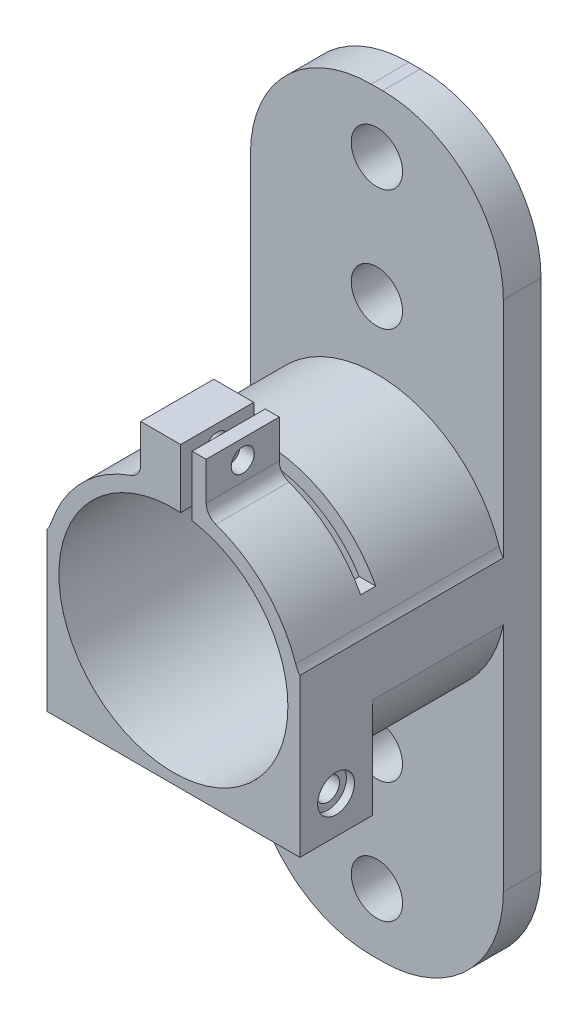
SolidWorks part; units mm, degrees
ref_plane "Front Plane" through (0, 0, 0) normal (0, 0, 1) x (1, 0, 0)
ref_plane "Top Plane" through (0, 0, 0) normal (0, 1, 0) x (1, 0, 0)
ref_plane "Right Plane" through (0, 0, 0) normal (1, 0, 0) x (0, 0, -1)
sketch "Sketch1" plane through (0, 0, 0) normal (0, 0, 1) x (1, 0, 0)
  line L0 (-13.97, 0) -> (13.97, 0)
  line L1 (13.97, 0) -> (13.97, 17.4151)
  line L2 (13.97, 28.0162) -> (-13.97, 28.0162) construction
  line L3 (-13.97, 17.4151) -> (-13.97, 0)
  line L4 (0, 0) -> (0, 32.6948) construction
  arc A0 (13.5022, 18.2934) -> (-13.5022, 18.2934) centre (0, 13.7795) ccw
  arc A1 (-13.97, 17.4151) -> (-13.5022, 18.2934) centre (-16.3447, 19.2437) ccw
  arc A2 (13.97, 17.4151) -> (13.5022, 18.2934) centre (16.3447, 19.2437) cw
  dimension "D4" = 28.4734
  dimension "D6" = 5.9944
  dimension "D1" = 27.94
  dimension "D2" = 13.97
  dimension "D3" = 28.0162
  dimension "D5" = 13.7795
extrude "Boss-Extrude1" add sketch "Sketch1" against normal blind 55.499
sketch "Sketch2" plane through (0, 0, 0) normal (0, 0, 1) x (1, 0, 0)
  circle A0 centre (0, 13.7795) radius 12.6492
  dimension "D1" = 25.2984
extrude "Cut-Extrude1" cut sketch "Sketch2" against normal blind 21.082
sketch "Sketch3" plane through (0, 0, -55.499) normal (0, 0, -1) x (-1, 0, 0)
  line L0 (-13.97, 0) -> (-13.97, 17.4151) construction
  line L1 (13.97, 0) -> (-13.97, 0) construction
  line L2 (13.97, 17.4151) -> (13.97, 0) construction
  line L3 (-13.97, 0) -> (-13.97, 11.0367)
  line L4 (13.97, 0) -> (3.579, 0)
  line L5 (13.97, 11.0367) -> (13.97, 0)
  line L6 (-3.579, 0) -> (-13.97, 0)
  arc A0 (-13.97, 11.0367) -> (-3.579, 0) centre (0, 13.7795) ccw
  arc A1 (3.579, 0) -> (13.97, 11.0367) centre (0, 13.7795) ccw
extrude "Cut-Extrude2" cut sketch "Sketch3" against normal blind 47.498
sketch "Sketch4" plane through (0, 0, 0) normal (0, 1, 0) x (1, 0, 0)
  line L0 (0, 60.4988) -> (0, 6.2072) construction
  line L1 (-10.033, 46.5201) -> (-10.033, 26.4795)
  line L2 (10.033, 46.5201) -> (10.033, 26.4795)
  line L3 (-6.0325, 50.5206) -> (6.0325, 50.5206)
  line L4 (6.0325, 22.479) -> (-6.0325, 22.479)
  line L5 (-10.033, 60.4988) -> (-10.033, 6.2072) construction
  line L6 (10.033, 60.4988) -> (10.033, 6.2072) construction
  line L7 (13.5022, 55.499) -> (-13.5022, 55.499) construction
  line L8 (-13.5022, 0) -> (13.5022, 0) construction
  arc A0 (-10.033, 46.5201) -> (-6.0325, 50.5206) centre (-6.0325, 46.5201) cw
  arc A1 (6.0325, 50.5206) -> (10.033, 46.5201) centre (6.0325, 46.5201) cw
  arc A2 (10.033, 26.4795) -> (6.0325, 22.479) centre (6.0325, 26.4795) cw
  arc A3 (-6.0325, 22.479) -> (-10.033, 26.4795) centre (-6.0325, 26.4795) cw
  dimension "D5" = 4.0005
  dimension "D3" = 4.9784
  dimension "D4" = 22.479
  dimension "D1" = 10.033
  dimension "D2" = 10.033
extrude "Cut-Extrude3" cut sketch "Sketch4" along normal through all
sketch "Sketch5" plane through (13.97, 0, 0) normal (1, 0, 0) x (0, 0, -1)
  line L0 (22.479, 26.6749) -> (22.479, 0.8841) construction
  line L1 (22.479, 30.5529) -> (22.479, 23.1262)
  line L2 (26.479, 19.1262) -> (58.3801, 19.1262)
  line L3 (22.479, 28.0162) -> (0, 28.0162) construction
  line L4 (22.479, 30.5529) -> (58.3801, 30.5529)
  line L5 (58.3801, 30.5529) -> (58.3801, 19.1262)
  arc A0 (26.479, 19.1262) -> (22.479, 23.1262) centre (26.479, 23.1262) cw
  dimension "D2" = 4
  dimension "D1" = 8.89
extrude "Cut-Extrude4" cut sketch "Sketch5" against normal through all
sketch "Sketch6" plane through (13.97, 0, 0) normal (1, 0, 0) x (0, 0, -1)
  line L0 (26.479, 5.7404) -> (41.275, 5.7404)
  line L1 (26.479, 19.1262) -> (55.499, 19.1262) construction
  line L2 (22.479, 23.1262) -> (22.479, 28.0162) construction
  line L3 (22.479, -1.6814) -> (22.479, 1.7404)
  line L4 (22.479, -1.6814) -> (56.8508, -1.6814)
  line L5 (56.8508, -1.6814) -> (56.8508, 10.8013)
  line L6 (41.275, 5.7404) -> (56.8508, 10.8013)
  line L7 (0, 0) -> (0, 17.4151) construction
  arc A0 (26.479, 5.7404) -> (22.479, 1.7404) centre (26.479, 1.7404) ccw
  dimension "D2" = 4
  dimension "D1" = 13.3858
  dimension "D3" = 18
  dimension "D4" = 41.275
extrude "Cut-Extrude5" cut sketch "Sketch6" against normal through all
fillet "Fillet1" radius 4.9911 1 edges at (0, 19.1262, -55.499)
fillet "Fillet2" radius 4.9911 1 edges at (0, 10.3621, -55.499)
sketch "Sketch7" plane through (13.97, 0, 0) normal (1, 0, 0) x (0, 0, -1)
  line L0 (10.541, 26.4287) -> (10.541, 1.1303) construction
  line L1 (21.082, 26.4287) -> (0, 26.4287) construction
  line L2 (0, 1.1303) -> (21.082, 1.1303) construction
  line L3 (55.499, 14.0617) -> (48.6594, 14.0617) construction
  line L4 (55.499, 13.9883) -> (55.499, 14.1351) construction
  circle A0 centre (50.5079, 14.0617) radius 1.27
  dimension "D1" = 2.54
  dimension "D2" = 4.9911
extrude "Cut-Extrude6" cut sketch "Sketch7" against normal blind 4.826
sketch "Sketch8" plane through (-13.97, 0, 0) normal (-1, 0, 0) x (0, 0, 1)
  circle A0 centre (-50.5079, 14.0617) radius 1.27 construction
  circle A1 centre (-50.5079, 14.0617) radius 1.27
extrude "Cut-Extrude7" cut sketch "Sketch8" against normal blind 4.826
sketch "Sketch9" plane through (13.97, 0, 0) normal (1, 0, 0) x (0, 0, -1)
  line L0 (4.0005, 0) -> (4.0005, 8.2081) construction
  line L1 (8.001, 0) -> (0, 0) construction
  circle A0 centre (4.0005, 4.1148) radius 1.27
  dimension "D1" = 2.54
  dimension "D2" = 4.1148
extrude "Cut-Extrude8" cut sketch "Sketch9" against normal blind 4.318
sketch "Sketch10" plane through (-13.97, 0, 0) normal (-1, 0, 0) x (0, 0, 1)
  circle A0 centre (-4.0005, 4.1148) radius 1.27 construction
  circle A1 centre (-4.0005, 4.1148) radius 1.27
extrude "Cut-Extrude9" cut sketch "Sketch10" against normal blind 4.318
sketch "Sketch11" plane through (-13.97, 0, 0) normal (-1, 0, 0) x (0, 0, 1)
  line L0 (-8.0772, 28.0162) -> (-8.0772, 20.3962)
  line L1 (0, 17.4151) -> (0, 0) construction
  line L2 (-9.7536, 28.0162) -> (-9.7536, 20.3962)
  line L3 (-9.7536, 20.3962) -> (-8.0772, 20.3962)
  line L4 (0, 28.0162) -> (-22.479, 28.0162) construction
  line L5 (-8.0772, 28.0162) -> (-9.7536, 28.0162)
  line L6 (-9.7536, 30.5529) -> (-9.7536, 20.2358) construction
  line L7 (-8.0772, 30.5529) -> (-8.0772, 20.2358) construction
  dimension "D1" = 8.0772
  dimension "D3" = 7.62
  dimension "D2" = 1.6764
extrude "Cut-Extrude10" cut sketch "Sketch11" against normal through all
sketch "Sketch12" plane through (0, 0, 0) normal (0, 0, 1) x (1, 0, 0)
  line L0 (-3.6195, 32.9184) -> (3.6195, 32.9184)
  line L1 (-13.97, 0) -> (13.97, 0) construction
  line L2 (0, 41.8243) -> (0, 22.9398) construction
  line L3 (-3.6195, 32.9184) -> (-3.6195, 27.5484)
  line L4 (3.6195, 32.9184) -> (3.6195, 27.5484)
  line L5 (-3.6195, 41.8243) -> (-3.6195, 22.9398) construction
  line L6 (3.6195, 41.8243) -> (3.6195, 22.9398) construction
  arc A0 (13.5022, 18.2934) -> (-13.5022, 18.2934) centre (0, 13.7795) ccw construction
  arc A1 (3.6195, 27.5484) -> (-3.6195, 27.5484) centre (0, 13.7795) ccw
  dimension "D1" = 32.9184
  dimension "D2" = 3.6195
  dimension "D3" = 3.6195
extrude "Boss-Extrude2" add sketch "Sketch12" against normal up to surface (8.0772 mm away) up to face at (0, 23.8093, -8.0772)
sketch "Sketch13" plane through (0, 0, 0) normal (0, 0, 1) x (1, 0, 0)
  line L0 (2.0701, 33.5492) -> (2.0701, 24.8503)
  line L1 (2.0701, 33.5492) -> (0.8001, 33.5492)
  line L2 (0.8001, 33.5492) -> (0.8001, 24.8503)
  line L3 (0.8001, 24.8503) -> (2.0701, 24.8503)
  line L4 (-3.6195, 32.9184) -> (-3.6195, 27.5484) construction
  dimension "D1" = 1.27
  dimension "D2" = 4.4196
extrude "Cut-Extrude11" cut sketch "Sketch13" against normal up to surface (8.0772 mm away) up to face at (0, 26.3055, -8.0772)
fillet "Fillet3" radius 1.5875 2 edges at (3.6195, 27.5484, -4.0386) (-3.6195, 27.5484, -4.0386)
sketch "Sketch14" plane through (3.6195, 0, 0) normal (1, 0, 0) x (0, 0, -1)
  line L0 (4.0386, 32.9184) -> (4.0386, 28.7225) construction
  line L2 (8.0772, 32.9184) -> (0, 32.9184) construction
  line L3 (0, 28.7225) -> (8.0772, 28.7225) construction
  circle A0 centre (4.0386, 30.8204) radius 1.27
  dimension "D1" = 2.54
extrude "Cut-Extrude12" cut sketch "Sketch14" against normal through all
sketch "Sketch15" plane through (13.97, 0, 0) normal (1, 0, 0) x (0, 0, -1)
  circle A0 centre (4.0005, 4.1148) radius 2.032
  circle A1 centre (50.5079, 14.0617) radius 2.032
  dimension "D1" = 4.064
  dimension "D2" = 4.064
extrude "Cut-Extrude13" cut sketch "Sketch15" against normal blind 0.889
sketch "Sketch16" plane through (-13.97, 0, 0) normal (-1, 0, 0) x (0, 0, 1)
  circle A0 centre (-50.5079, 14.0617) radius 2.032 construction
  circle A1 centre (-4.0005, 4.1148) radius 2.032 construction
  circle A2 centre (-50.5079, 14.0617) radius 2.032
  circle A3 centre (-4.0005, 4.1148) radius 2.032
extrude "Cut-Extrude14" cut sketch "Sketch16" against normal blind 0.889
scale "Scale1" scale about centroid uniform scaling yes scale factor 0.6
sketch "Sketch17" plane through (0, 0, 0) normal (0, 1, 0) x (1, 0, 0)
  line L0 (6.439, 23.6599) -> (-6.4476, 23.6599) construction
  line L1 (-10.1977, 23.6599) -> (12.3965, 23.6599)
  line L2 (-10.1977, 23.6599) -> (-10.1977, 45.7128)
  line L3 (-10.1977, 45.7128) -> (12.3965, 45.7128)
  line L4 (12.3965, 23.6599) -> (12.3965, 45.7128)
extrude "Cut-Extrude15" cut sketch "Sketch17" against normal through all both and the other way through all
sketch "Sketch18" plane through (0, 0, -23.6599) normal (0, 0, -1) x (-1, 0, 0)
  line L1 (8.3863, 38.5769) -> (-8.3777, 38.5769)
  line L2 (8.3863, 38.5769) -> (8.3863, -11.4231)
  line L3 (8.3863, -11.4231) -> (-8.3777, -11.4231)
  line L4 (-8.3777, 38.5769) -> (-8.3777, -11.4231)
  line L5 (8.3863, 38.5769) -> (-8.3777, -11.4231) construction
  line L6 (8.3863, -11.4231) -> (-8.3777, 38.5769) construction
  point P0 (0.0043, 13.5769)
  dimension "D1" = 50
extrude "Boss-Extrude3" add sketch "Sketch18" along normal blind 2.5
fillet "Fillet4" radius 8 4 edges at (8.3777, 38.5769, -24.9099) (-8.3863, 38.5769, -24.9099) (8.3777, -11.4231, -24.9099) (-8.3863, -11.4231, -24.9099)
hole_wizard "M3 Clearance Hole1" positions "Sketch19" profile "Sketch20" hole size "M3" standard "ANSI Metric"
sketch "Sketch19" plane through (0, 0, -23.6599) normal (0, 0, 1) x (1, 0, 0)
  line L0 (-0.0043, -11.4231) -> (-0.0043, 38.5769) construction
  line L1 (0.3777, -11.4231) -> (-0.3863, -11.4231) construction
  line L2 (-0.3863, 38.5769) -> (0.3777, 38.5769) construction
  point P8 (-0.0043, -7.4231)
  point P10 (-0.0043, 0.5769)
  point P12 (-0.0043, 34.5769)
  point P14 (-0.0043, 26.5769)
  dimension "D1" = 8
  dimension "D2" = 4
  dimension "D3" = 8
  dimension "D4" = 4
sketch "Sketch20" plane through (-0.0043, 26.5769, -23.6599) normal (1, 0, 0) x (0, -1, 0)
  line L0 (0, 0) -> (0, 2.5)
  line L1 (0, 2.5) -> (1.7, 2.5)
  line L2 (1.7, 2.5) -> (1.7, 0)
  line L5 (1.7, 0) -> (0, 0)
  line L11 (0, -6.35) -> (0, 107.95) construction
  dimension "Thru Hole Dia." = 3.4
  dimension "Thru Hole Depth" = 2.5
